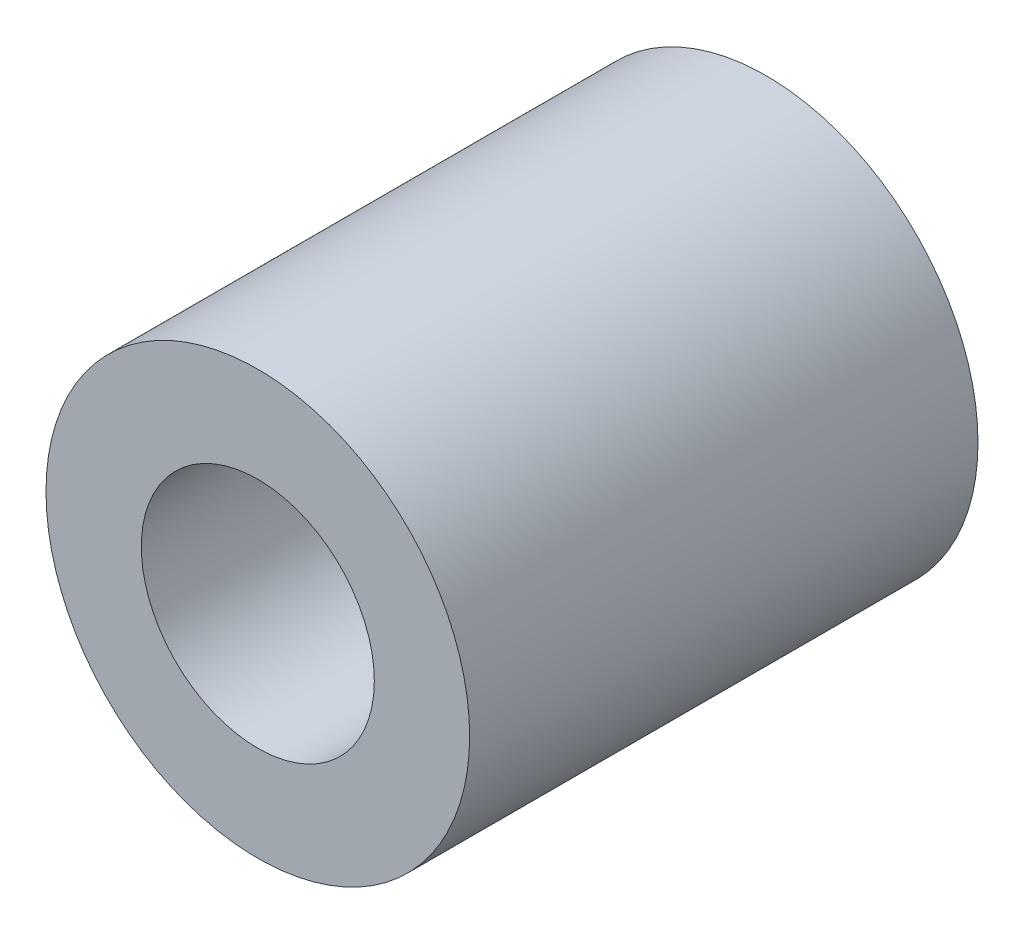
SolidWorks part; units mm, degrees
ref_plane "Front Plane" through (0, 0, 0) normal (0, 0, 1) x (1, 0, 0)
ref_plane "Top Plane" through (0, 0, 0) normal (0, 1, 0) x (1, 0, 0)
ref_plane "Right Plane" through (0, 0, 0) normal (1, 0, 0) x (0, 0, -1)
sketch "Sketch1" plane through (0, 0, 0) normal (0, 0, 1) x (1, 0, 0)
  circle A0 centre (0, 0) radius 2.75
  circle A1 centre (0, 0) radius 5
  dimension "D1" = 5.5
  dimension "D2" = 10
extrude "Boss-Extrude1" add sketch "Sketch1" along normal blind 12
